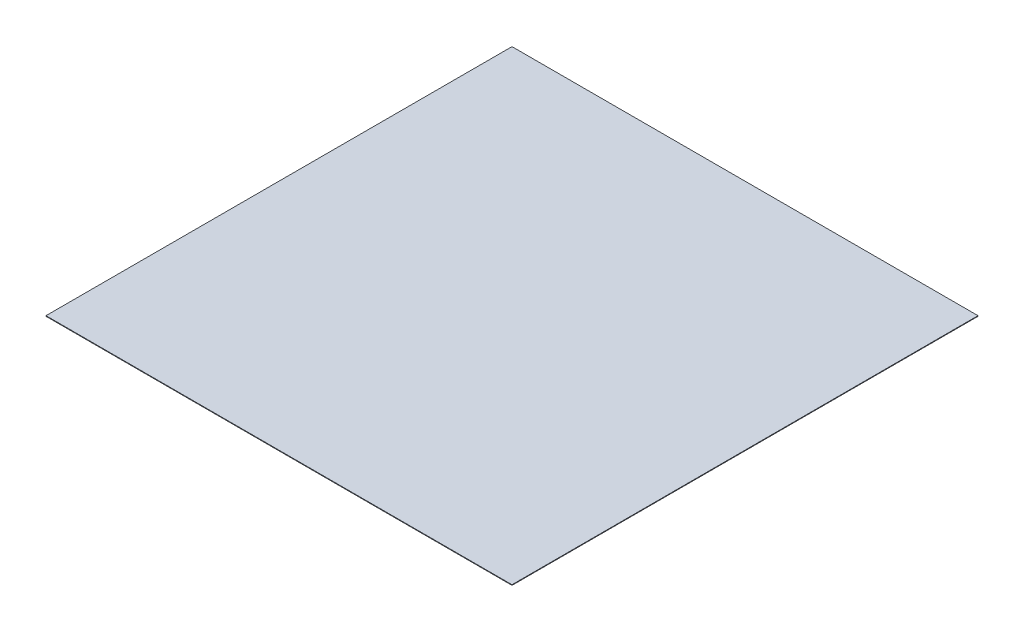
SolidWorks part; units mm, degrees
ref_plane "Alzado" through (0, 0, 0) normal (0, 0, 1) x (1, 0, 0)
ref_plane "Planta" through (0, 0, 0) normal (0, 1, 0) x (1, 0, 0)
ref_plane "Vista lateral" through (0, 0, 0) normal (1, 0, 0) x (0, 0, -1)
sketch "Croquis1" plane through (0, 0, 0) normal (0, 0, 1) x (1, 0, 0)
  line L0 (-229.6314, -78.1667) -> (7770.3686, -78.1667)
  line L1 (7770.3686, -78.1667) -> (7770.3686, -68.1667)
  line L2 (7770.3686, -68.1667) -> (-229.6314, -68.1667)
  line L3 (-229.6314, -68.1667) -> (-229.6314, -78.1667)
  point P3 (3770.3686, -78.1667)
  dimension "D1" = 10
  dimension "D2" = 8000
extrude "Saliente-Extruir1" add sketch "Croquis1" along normal blind 8000
